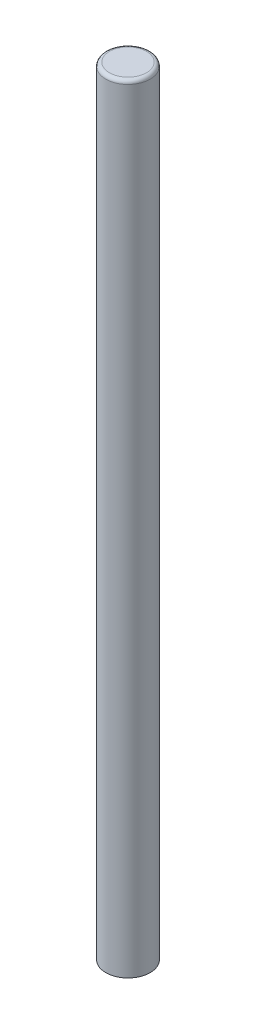
SolidWorks part; units mm, degrees
ref_plane "Front Plane" through (0, 0, 0) normal (0, 0, 1) x (1, 0, 0)
ref_plane "Top Plane" through (0, 0, 0) normal (0, 1, 0) x (1, 0, 0)
ref_plane "Right Plane" through (0, 0, 0) normal (1, 0, 0) x (0, 0, -1)
sketch "Sketch1" plane through (0, 0, 0) normal (0, 1, 0) x (1, 0, 0)
  circle A0 centre (0, 0) radius 3
  dimension "D1" = 6
extrude "Boss-Extrude1" add sketch "Sketch1" along normal blind 105
fillet "Fillet1" radius 0.5 1 edges at (0, 105, 3)
